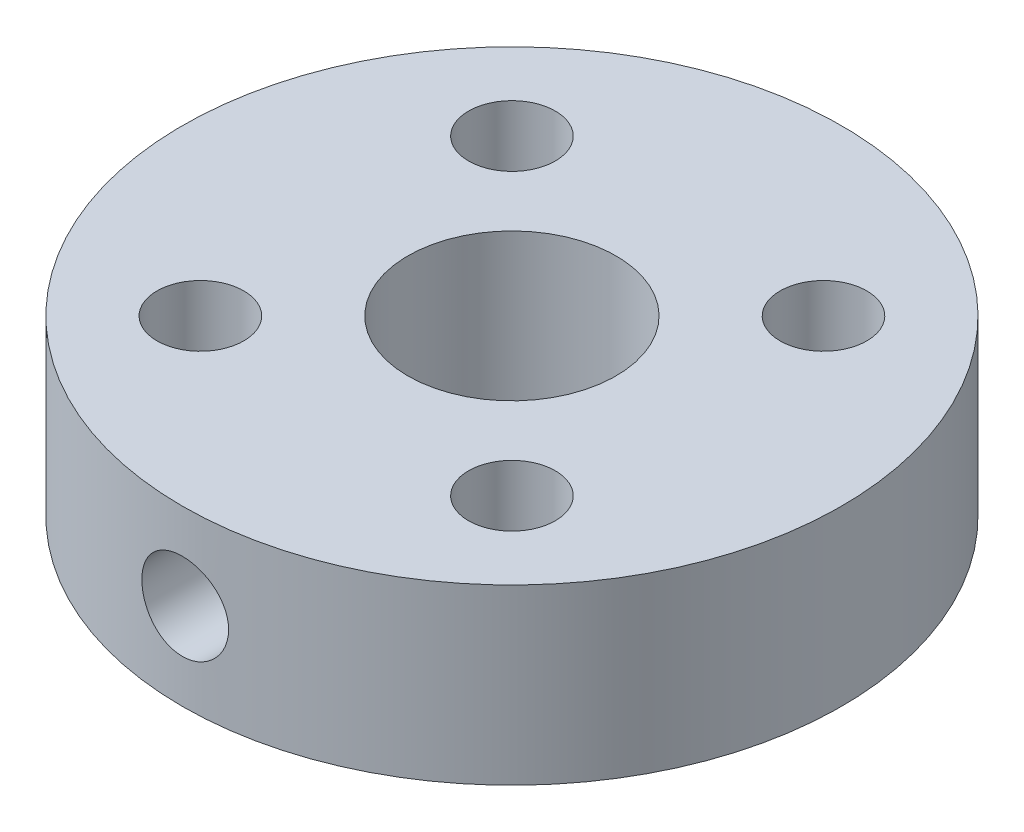
SolidWorks part; units mm, degrees
ref_plane "Front" through (0, 0, 0) normal (0, 0, 1) x (1, 0, 0)
ref_plane "Top" through (0, 0, 0) normal (0, 1, 0) x (1, 0, 0)
ref_plane "Right" through (0, 0, 0) normal (1, 0, 0) x (0, 0, -1)
sketch "Sketch1" plane through (0, 0, 0) normal (0, 1, 0) x (1, 0, 0)
  circle A0 centre (0, 0) radius 9.5
  dimension "D1" = 19
extrude "Boss-Extrude1" add sketch "Sketch1" along normal blind 5
hole_wizard "Ø6.0mm Dowel Hole1" positions "Sketch2" profile "Sketch3" hole size "Ø6.0" standard "ANSI Metric" end condition through all
sketch "Sketch2" plane through (0, 5, 0) normal (0, 1, 0) x (1, 0, 0)
  point P0 (0, 0)
sketch "Sketch3" plane through (0, 5, 0) normal (1, 0, 0) x (0, 0, 1)
  line L0 (0, 0) -> (0, 5)
  line L1 (0, 5) -> (3, 5)
  line L2 (3, 5) -> (3, 0)
  line L5 (3, 0) -> (0, 0)
  line L11 (0, -6.35) -> (0, 107.95) construction
  dimension "Thru Hole Dia." = 6
  dimension "Thru Hole Depth" = 5
hole_wizard "M3x0.5 Tapped Hole1" positions "Sketch4" profile "Sketch5" tap size "M3x0.5" standard "ANSI Metric" end condition through all
sketch "Sketch4" plane through (0, 5, 0) normal (0, 1, 0) x (1, 0, 0)
  line L0 (0, 0) -> (4.4901, 4.4901) construction
  line L3 (0, 0) -> (-4.4901, 4.4901) construction
  line L6 (0, 0) -> (-4.4901, -4.4901) construction
  line L9 (0, 0) -> (4.4901, -4.4901) construction
  line L10 (0, 0) -> (4.8926, 0) construction
  point P0 (4.4901, 4.4901)
  point P2 (-4.4901, 4.4901)
  point P4 (-4.4901, -4.4901)
  point P6 (4.4901, -4.4901)
  dimension "D1" = 45
  dimension "D2" = 6.35
  dimension "D3" = 90
sketch "Sketch5" plane through (4.4901, 5, -4.4901) normal (1, 0, 0) x (0, 0, 1)
  line L0 (0, 0) -> (0, 5)
  line L1 (0, 5) -> (1.25, 5)
  line L2 (1.25, 5) -> (1.25, 0)
  line L5 (1.25, 0) -> (0, 0)
  line L11 (0, -6.35) -> (0, 107.95) construction
  dimension "Thru Tap Drill Dia." = 2.5
  dimension "Thru Tap Drill Depth" = 5
cosmetic thread "Hole Thread1" parameters "D2"=3
cosmetic thread "Hole Thread2" parameters "D2"=3
cosmetic thread "Hole Thread3" parameters "D2"=3
cosmetic thread "Hole Thread4" parameters "D2"=3
hole_wizard "M3x0.5 Tapped Hole2" positions "3DSketch1" profile "Sketch7" tap size "M3x0.5" standard "ANSI Metric"
sketch3d "3DSketch1"
  line L2 (0, 0, 0) -> (0, 2.5, 0) construction
  point P0 (0, 2.5, 9.5)
  dimension "D1" = 2.5
sketch "Sketch7" plane through (0, 2.5, 9.5) normal (1, 0, 0) x (0, -1, 0)
  line L0 (0, 0) -> (0, 10.7511)
  line L1 (0, 10.7511) -> (1.25, 10)
  line L2 (1.25, 10) -> (1.25, 0)
  line L5 (1.25, 0) -> (0, 0)
  line L10 (0, 10.7511) -> (-1.25, 10) construction
  line L11 (0, -6.35) -> (0, 107.95) construction
  dimension "Tap Drill Dia." = 2.5
  dimension "Tap Drill Depth" = 10
  dimension "Drill Angle" = 118
cosmetic thread "Hole Thread5" parameters "D1"=10, "D2"=3
